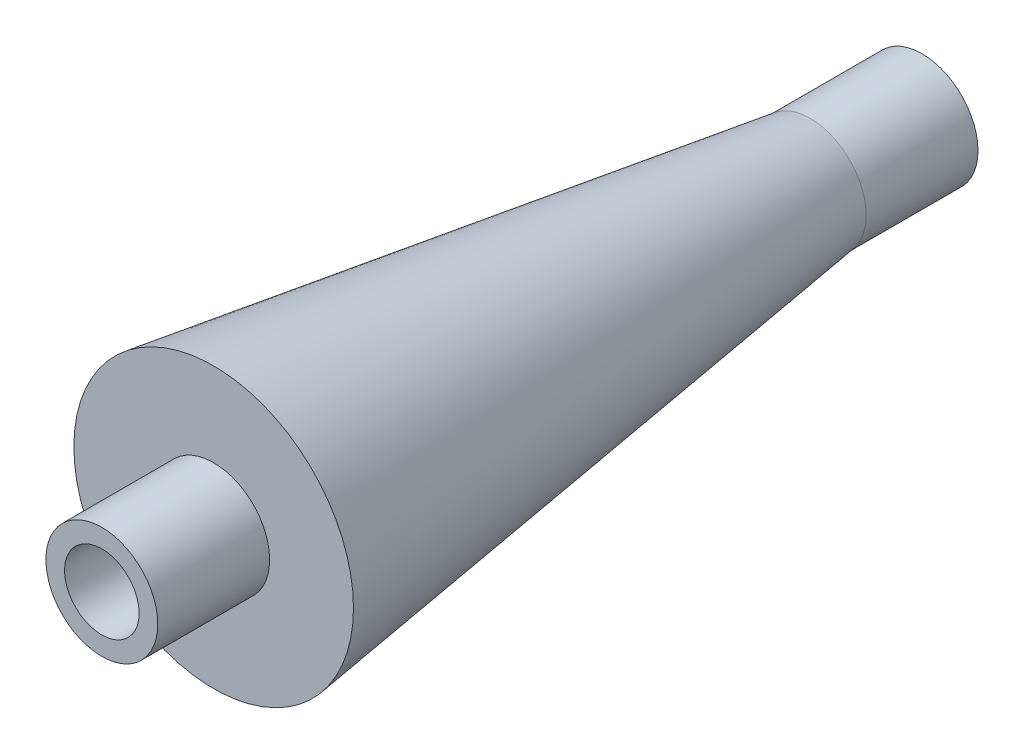
SolidWorks part; units mm, degrees
material "6061-T6 (SS)"
ref_plane "Front Plane" through (0, 0, 0) normal (0, 0, 1) x (1, 0, 0)
ref_plane "Top Plane" through (0, 0, 0) normal (0, 1, 0) x (1, 0, 0)
ref_plane "Right Plane" through (0, 0, 0) normal (1, 0, 0) x (0, 0, -1)
sketch "Sketch1" plane through (0, 0, 0) normal (0, 1, 0) x (1, 0, 0)
  line L0 (4.7625, 23.9683) -> (4.7625, 14.4433) construction
  line L1 (4.7625, 14.4433) -> (-4.7625, 14.4433) construction
  line L2 (11.9063, 23.9683) -> (-11.9062, 23.9683) construction
  line L3 (4.7625, 84.2933) -> (-4.7625, 84.2933) construction
  line L4 (4.7625, 74.7683) -> (4.7625, 84.2933) construction
  line L5 (4.7625, 74.7683) -> (11.9063, 23.9683) construction
  line L7 (4.7625, 23.9683) -> (4.7625, 14.4433)
  line L8 (4.7625, 14.4433) -> (3.175, 14.4433)
  line L9 (11.9063, 23.9683) -> (4.7625, 23.9683)
  line L10 (4.7625, 84.2933) -> (3.175, 84.2933)
  line L11 (4.7625, 74.7683) -> (4.7625, 84.2933)
  line L12 (4.7625, 74.7683) -> (11.9063, 23.9683)
  line L14 (3.175, -1.5875) -> (3.175, 99.7956) construction
  line L15 (3.175, 14.4433) -> (3.175, 84.2933)
  line L16 (0, -1.5875) -> (0, 99.7956) construction
  line L17 (0, -1.5875) -> (0, 99.7956)
revolve "Revolve1" add sketch "Sketch1" angle 360 about L17
